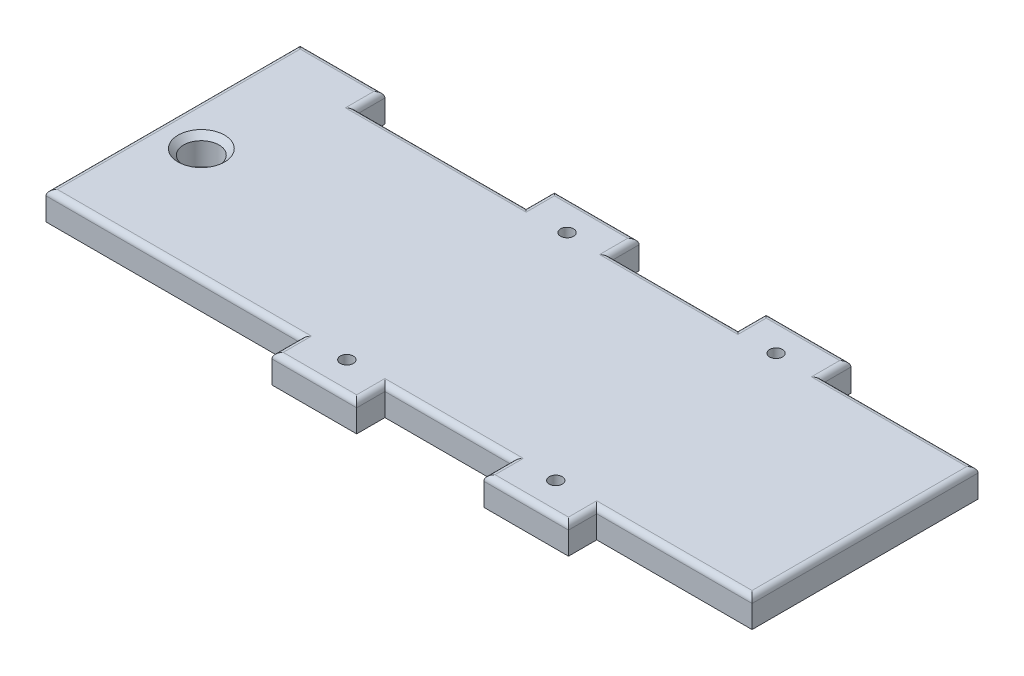
SolidWorks part; units mm, degrees
ref_plane "Front Plane" through (0, 0, 0) normal (0, 0, 1) x (1, 0, 0)
ref_plane "Top Plane" through (0, 0, 0) normal (0, 1, 0) x (1, 0, 0)
ref_plane "Right Plane" through (0, 0, 0) normal (1, 0, 0) x (0, 0, -1)
sketch "Sketch1" plane through (0, 0, 0) normal (0, 1, 0) x (1, 0, 0)
  line L1 (130, -50) -> (-130, -50)
  line L2 (130, -50) -> (130, 50)
  line L3 (130, 50) -> (-130, 50)
  line L4 (-130, -50) -> (-130, 50)
  line L5 (0, 50) -> (0, -50) construction
  line L6 (130, 0) -> (-130, 0) construction
  point P0 (0, 0)
  dimension "D1" = 260
  dimension "D2" = 100
extrude "Boss-Extrude1" add sketch "Sketch1" along normal blind 10
sketch "Sketch3" plane through (0, 10, 0) normal (0, 1, 0) x (1, 0, 0)
  line L0 (130, 50) -> (-130, 50) construction
  line L1 (130, 50) -> (75, 50)
  line L2 (130, 50) -> (130, 40)
  line L3 (130, 40) -> (75, 40)
  line L4 (75, 50) -> (75, 40)
  line L5 (130, -50) -> (75, -50)
  line L6 (130, -50) -> (130, -40)
  line L7 (130, -40) -> (75, -40)
  line L8 (75, -50) -> (75, -40)
  line L9 (-130, -50) -> (-30, -50)
  line L10 (-130, -50) -> (-130, -40)
  line L11 (-120, -40) -> (-30, -40)
  line L12 (-30, -50) -> (-30, -40)
  line L13 (-90, 50) -> (-30, 50)
  line L14 (-90, 50) -> (-90, 40)
  line L15 (-90, 40) -> (-30, 40)
  line L16 (-30, 50) -> (-30, 40)
  line L17 (-130, 50) -> (-130, -50) construction
  line L18 (-130, -50) -> (130, -50) construction
  line L19 (0, 50) -> (45, 50)
  line L20 (0, 50) -> (0, 40)
  line L21 (0, 40) -> (45, 40)
  line L22 (45, 50) -> (45, 40)
  line L23 (0, -50) -> (45, -50)
  line L24 (0, -50) -> (0, -40)
  line L25 (0, -40) -> (45, -40)
  line L26 (45, -50) -> (45, -40)
  line L28 (-130, 50) -> (-120, 50)
  line L29 (-130, 50) -> (-130, -40)
  line L31 (-120, 50) -> (-120, -40)
  dimension "D1" = 10
  dimension "D2" = 55
  dimension "D3" = 55
  dimension "D4" = 10
  dimension "D5" = 10
  dimension "D6" = 100
  dimension "D7" = 10
  dimension "D8" = 60
  dimension "D9" = 40
  dimension "D10" = 10
  dimension "D11" = 45
  dimension "D12" = 30
  dimension "D13" = 10
  dimension "D14" = 45
  dimension "D15" = 10
extrude "Cut-Extrude2" cut sketch "Sketch3" against normal through all
sketch "Sketch4" plane through (0, 10, 0) normal (0, 1, 0) x (1, 0, 0)
  circle A0 centre (59.5, 39) radius 2.3
  circle A1 centre (-14.5, 39) radius 2.3
  circle A2 centre (59.5, -39) radius 2.3
  circle A3 centre (-14.5, -39) radius 2.3
  dimension "D1" = 4.6
  dimension "D2" = 4.6
  dimension "D3" = 4.6
  dimension "D4" = 4.6
fillet "Fillet1" radius 2 22 edges at (130, 10, 0) (-60, 10, -40) (-30, 10, -45) (-15, 10, -50) (60, 10, -50) (75, 10, -45) (102.5, 10, -40) (102.5, 10, 40) (75, 10, 45) (-30, 10, 45) (-75, 10, 40) (-90, 10, -45) (60, 10, 50) (45, 10, 45) (22.5, 10, 40) (0, 10, 45) (-15, 10, 50) (0, 10, -45) (22.5, 10, -40) (45, 10, -45) (-120, 10, -5) (-105, 10, -50)
sketch "Sketch2" plane through (0, 10, 0) normal (0, 1, 0) x (1, 0, 0)
  line L1 (-120, -40) -> (-120, 50) construction
  circle A0 centre (-105, 0) radius 6.25
  dimension "D2" = 12.5
  dimension "D1" = 15
extrude "Cut-Extrude1" cut sketch "Sketch2" against normal through all
chamfer "Chamfer1" distance 2 angle 45 1 edges at (-105, 10, 6.25)
extrude "Cut-Extrude3" cut sketch "Sketch4" against normal blind 6.2
